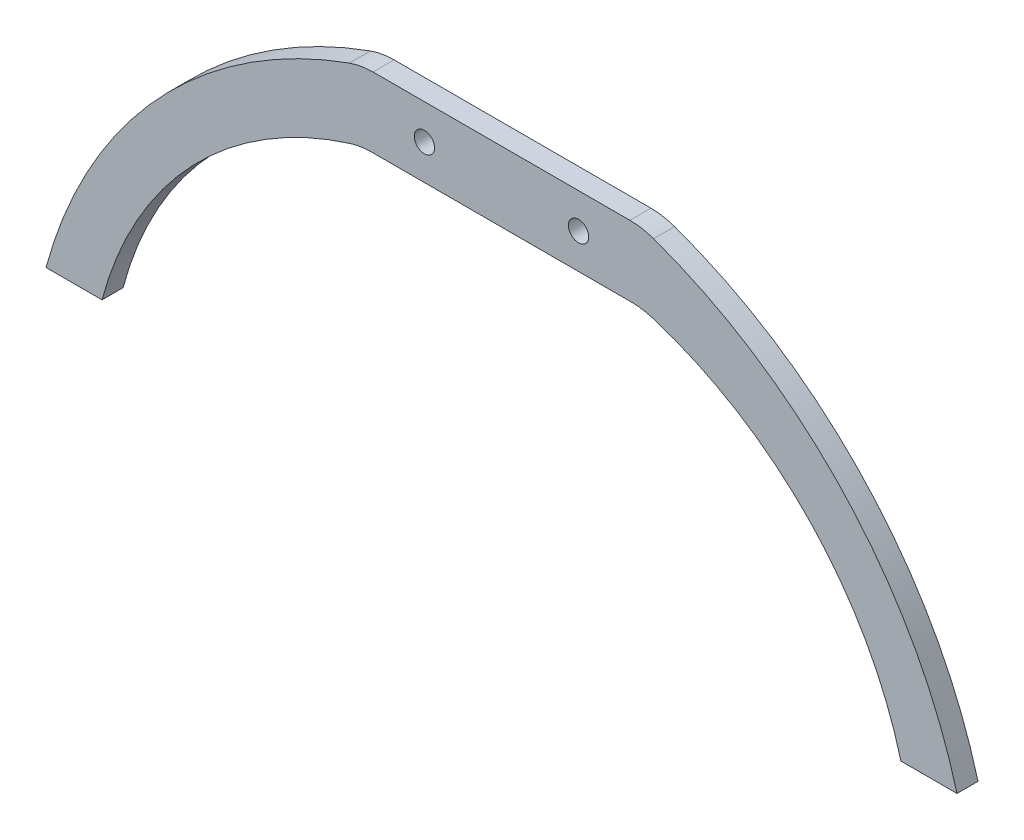
SolidWorks part; units mm, degrees
material "Thornel Mat VMA"
ref_plane "前视基准面" through (0, 0, 0) normal (0, 0, 1) x (1, 0, 0)
ref_plane "上视基准面" through (0, 0, 0) normal (0, 1, 0) x (1, 0, 0)
ref_plane "右视基准面" through (0, 0, 0) normal (1, 0, 0) x (0, 0, -1)
other "Configuration Table"
sketch "草图1" plane through (0, 0, 0) normal (0, 0, 1) x (1, 0, 0)
  line L0 (-73.4663, -37.5) -> (81.8369, -37.5) construction
  line L1 (-45, -37.5) -> (-37, -37.5)
  line L2 (0, 0) -> (40, 0)
  line L4 (0, 10) -> (40, 10)
  line L6 (77, -37.5) -> (85, -37.5)
  line L7 (20, 10) -> (20, -49.4863) construction
  arc A0 (-37, -37.5) -> (77, -37.5) centre (20, 92.036) ccw construction
  arc A1 (0, 10) -> (-45, -37.5) centre (21.6024, -55.5312) ccw
  arc A2 (-37, -37.5) -> (0, 0) centre (14.2382, -51.0517) cw
  arc A3 (40, 10) -> (85, -37.5) centre (18.3976, -55.5312) cw
  arc A4 (40, 0) -> (77, -37.5) centre (25.7618, -51.0517) cw
  point P18 (-45, -37.5)
  dimension "D7" = 69
  dimension "D8" = 53
  dimension "D1" = 37.5
  dimension "D2" = 10
  dimension "D3" = 40
  dimension "D4" = 8
  dimension "D5" = 8
  dimension "D6" = 130
extrude "凸台-拉伸1" add sketch "草图1" along normal blind 3
sketch "草图3" plane through (0, 0, 3) normal (0, 0, 1) x (1, 0, 0)
  line L0 (0, 0) -> (40, 0) construction
  line L1 (9, 5) -> (31, 5) construction
  line L2 (20, 5) -> (20, 0) construction
  circle A0 centre (9, 5) radius 1.45
  circle A1 centre (31, 5) radius 1.45
  dimension "D1" = 2.9
  dimension "D2" = 22
  dimension "D3" = 5
extrude "切除-拉伸2" cut sketch "草图3" against normal through all
fillet "圆角1" radius 10 4 edges at (40, 0, 1.5) (0, 0, 1.5) (40, 10, 1.5) (0, 10, 1.5)
